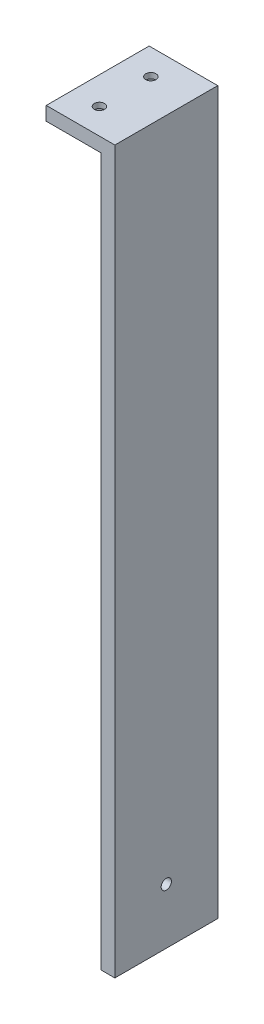
SolidWorks part; units mm, degrees
ref_plane "Plan de face" through (0, 0, 0) normal (0, 0, 1) x (1, 0, 0)
ref_plane "Plan de dessus" through (0, 0, 0) normal (0, 1, 0) x (1, 0, 0)
ref_plane "Plan de droite" through (0, 0, 0) normal (1, 0, 0) x (0, 0, -1)
sketch "Esquisse1" plane through (0, 0, 0) normal (0, 0, 1) x (1, 0, 0)
  line L0 (90.805, 44.0887) -> (116.205, 44.0887)
  line L1 (-116.205, 44.0887) -> (116.205, 44.0887) construction
  line L2 (116.205, 44.0887) -> (116.205, -223.0115)
  line L3 (106.045, -194.8492) -> (106.045, -251.1737) construction
  point P8 (106.045, -223.0115)
  dimension "D1" = 25.4
extrude "Extru.-Mince1" add sketch "Esquisse1" against normal up to surface (38.1 mm away) thin
sketch "Esquisse2" plane through (116.205, 0, 0) normal (1, 0, 0) x (0, 0, -1)
  circle A0 centre (19.05, -202.4692) radius 1.8986
  circle A1 centre (19.05, -202.4692) radius 1.8986 construction
extrude "Enlèv. mat.-Extru.1" cut sketch "Esquisse2" against normal through all
sketch "Esquisse3" plane through (0, 39.0087, 0) normal (0, -1, 0) x (1, 0, 0)
  line L0 (100.965, -28.575) -> (100.965, -9.525) construction
  line L1 (100.965, -23.7357) -> (96.774, -26.1553)
  line L2 (96.774, -26.1553) -> (96.774, -30.9947)
  line L3 (96.774, -30.9947) -> (100.965, -33.4143)
  line L4 (100.965, -33.4143) -> (105.156, -30.9947)
  line L5 (105.156, -30.9947) -> (105.156, -26.1553)
  line L6 (105.156, -26.1553) -> (100.965, -23.7357)
  line L7 (100.965, -4.6857) -> (96.774, -7.1053)
  line L8 (96.774, -7.1053) -> (96.774, -11.9447)
  line L9 (96.774, -11.9447) -> (100.965, -14.3643)
  line L10 (100.965, -14.3643) -> (105.156, -11.9447)
  line L11 (105.156, -11.9447) -> (105.156, -7.1053)
  line L12 (105.156, -7.1053) -> (100.965, -4.6857)
  line L13 (111.125, -38.1) -> (111.125, 0) construction
  line L14 (90.805, -38.1) -> (111.125, -38.1) construction
  line L15 (116.205, -38.1) -> (116.205, 0) construction
  circle A0 centre (100.965, -28.575) radius 4.191 construction
  circle A1 centre (100.965, -9.525) radius 4.191 construction
  point P18 (111.125, -19.05)
  point P19 (100.965, -19.05)
  point P22 (100.965, -38.1)
  dimension "D1" = 8.382
  dimension "D2" = 19.05
extrude "Enlèv. mat.-Extru.2" cut sketch "Esquisse3" against normal blind 3.048
hole_wizard "Dégagement #61" positions "Esquisse4" profile "Esquisse5" hole size "#6" standard "Ansi Inch" end condition through all
sketch "Esquisse4" plane through (0, 42.0567, 0) normal (0, -1, 0) x (-1, 0, 0)
  line L0 (-100.965, 38.1) -> (-100.965, 0) construction
  line L1 (-96.774, 7.1053) -> (-96.774, 11.9447) construction
  line L2 (-96.774, 26.1553) -> (-96.774, 30.9947) construction
  point P0 (-100.965, 28.575)
  point P4 (-100.965, 9.525)
  point P9 (-96.774, 9.525)
  point P10 (0, 0)
  point P13 (-96.774, 28.575)
sketch "Esquisse5" plane through (100.965, 42.0567, -28.575) normal (1, 0, 0) x (0, 0, -1)
  line L0 (0, 0) -> (0, 2.032)
  line L1 (0, 2.032) -> (1.8986, 2.032)
  line L2 (1.8986, 2.032) -> (1.8986, 0)
  line L5 (1.8986, 0) -> (0, 0)
  line L11 (0, -6.35) -> (0, 107.95) construction
  dimension "Diamètre du perçage jusqu'au prochain" = 3.7973
  dimension "Profondeur du perçage jusqu'au prochain" = 2.032
